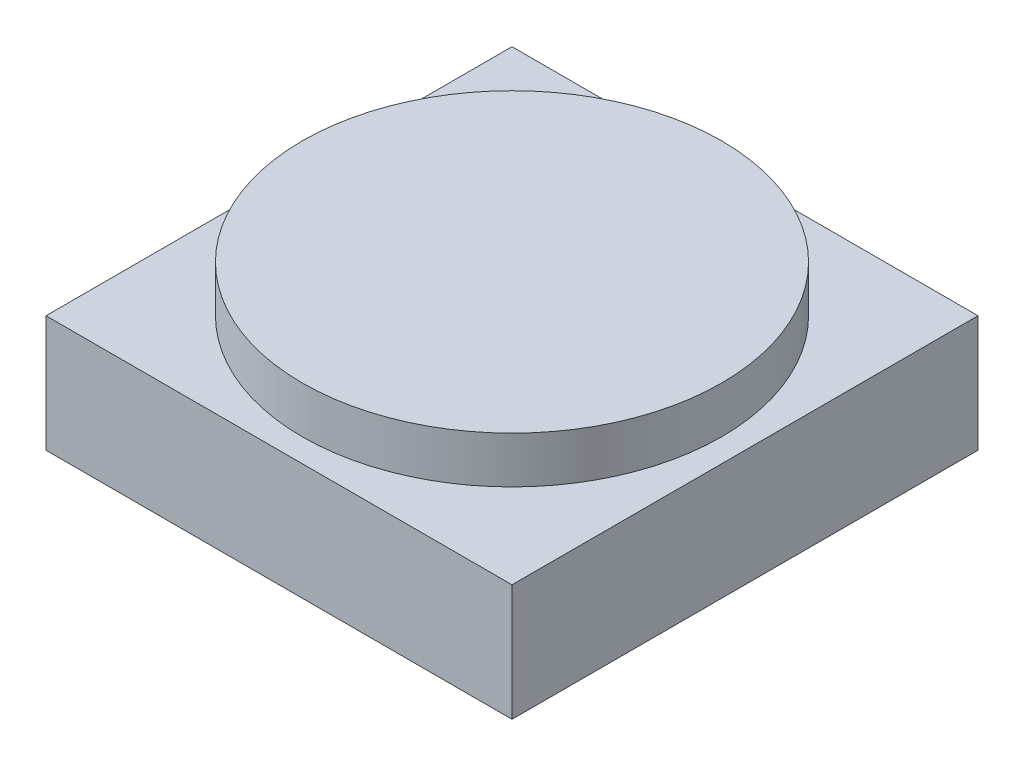
SolidWorks part; units mm, degrees
ref_plane "Front Plane" through (0, 0, 0) normal (0, 0, 1) x (1, 0, 0)
ref_plane "Top Plane" through (0, 0, 0) normal (0, 1, 0) x (1, 0, 0)
ref_plane "Right Plane" through (0, 0, 0) normal (1, 0, 0) x (0, 0, -1)
sketch "Sketch2" plane through (0, 0, 0) normal (0, 1, 0) x (1, 0, 0)
  line L1 (-15.875, -15.875) -> (15.875, -15.875)
  line L2 (-15.875, -15.875) -> (-15.875, 15.875)
  line L3 (-15.875, 15.875) -> (15.875, 15.875)
  line L4 (15.875, -15.875) -> (15.875, 15.875)
  line L5 (-15.875, -15.875) -> (15.875, 15.875) construction
  line L6 (-15.875, 15.875) -> (15.875, -15.875) construction
  point P0 (0, 0)
  dimension "D1" = 31.75
extrude "Boss-Extrude1" add sketch "Sketch2" along normal blind 7.9375
sketch "Sketch3" plane through (0, 7.9375, 0) normal (0, 1, 0) x (1, 0, 0)
  circle A0 centre (0, 0) radius 14.2875
  dimension "D1" = 28.575
extrude "Boss-Extrude2" add sketch "Sketch3" along normal blind 3.175 separate body
